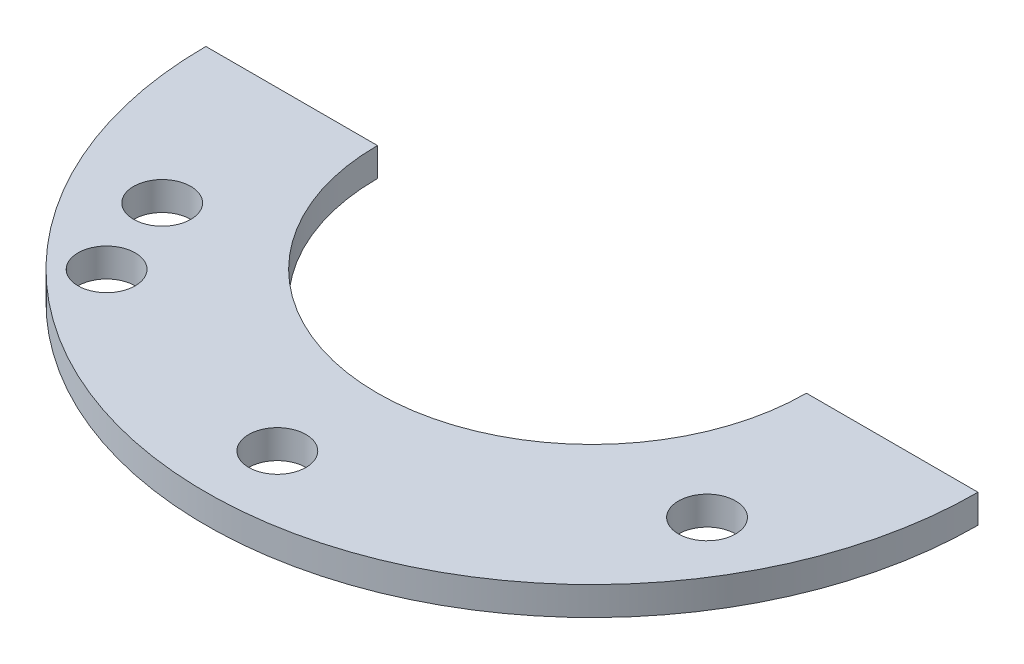
SolidWorks part; units mm, degrees
material "ABS"
ref_plane "Front Plane" through (0, 0, 0) normal (0, 0, 1) x (1, 0, 0)
ref_plane "Top Plane" through (0, 0, 0) normal (0, 1, 0) x (1, 0, 0)
ref_plane "Right Plane" through (0, 0, 0) normal (1, 0, 0) x (0, 0, -1)
sketch "Sketch1" plane through (0, 0, 0) normal (0, 1, 0) x (1, 0, 0)
  circle A0 centre (0, 0) radius 13.5
  dimension "D1" = 27
extrude "Boss-Extrude1" add sketch "Sketch1" along normal blind 1
sketch "Sketch19" plane through (0, 1, 0) normal (0, 1, 0) x (1, 0, 0)
  line L0 (0, 0) -> (-9.5263, -5.5) construction
  line L1 (-9.5263, -5.5) -> (0, 0) construction
  line L2 (0, 0) -> (-10.3586, -10.3586) construction
  circle A0 centre (0, 11) radius 1
  circle A1 centre (9.5263, 5.5) radius 1
  circle A2 centre (9.5263, -5.5) radius 1
  circle A3 centre (0, -11) radius 1
  circle A4 centre (-9.5263, -5.5) radius 1
  circle A5 centre (-9.5263, 5.5) radius 1
  circle A6 centre (-8.4853, -8.4853) radius 1
  point P13 (0, 0)
  point P17 (0, 0)
  dimension "D1" = 2
  dimension "D4" = 2
  dimension "D2" = 11
  dimension "D5" = 12
  dimension "D6" = 0
  dimension "D7" = 15
  dimension "D3" = 6
extrude "Cut-Extrude1" cut sketch "Sketch19" against normal through all both and the other way through all
sketch "Sketch20" plane through (0, 1, 0) normal (0, 1, 0) x (1, 0, 0)
  circle A0 centre (0, 0) radius 7.5
  dimension "D1" = 15
extrude "Cut-Extrude2" cut sketch "Sketch20" against normal through all both and the other way through all
sketch "Sketch21" plane through (0, 0, 0) normal (0, 0, 1) x (1, 0, 0)
  line L1 (-36.7533, 32.3113) -> (29.1209, 32.3113)
  line L2 (-36.7533, 32.3113) -> (-36.7533, -19.668)
  line L3 (-36.7533, -19.668) -> (29.1209, -19.668)
  line L4 (29.1209, 32.3113) -> (29.1209, -19.668)
extrude "Cut-Extrude3" cut sketch "Sketch21" against normal through all
